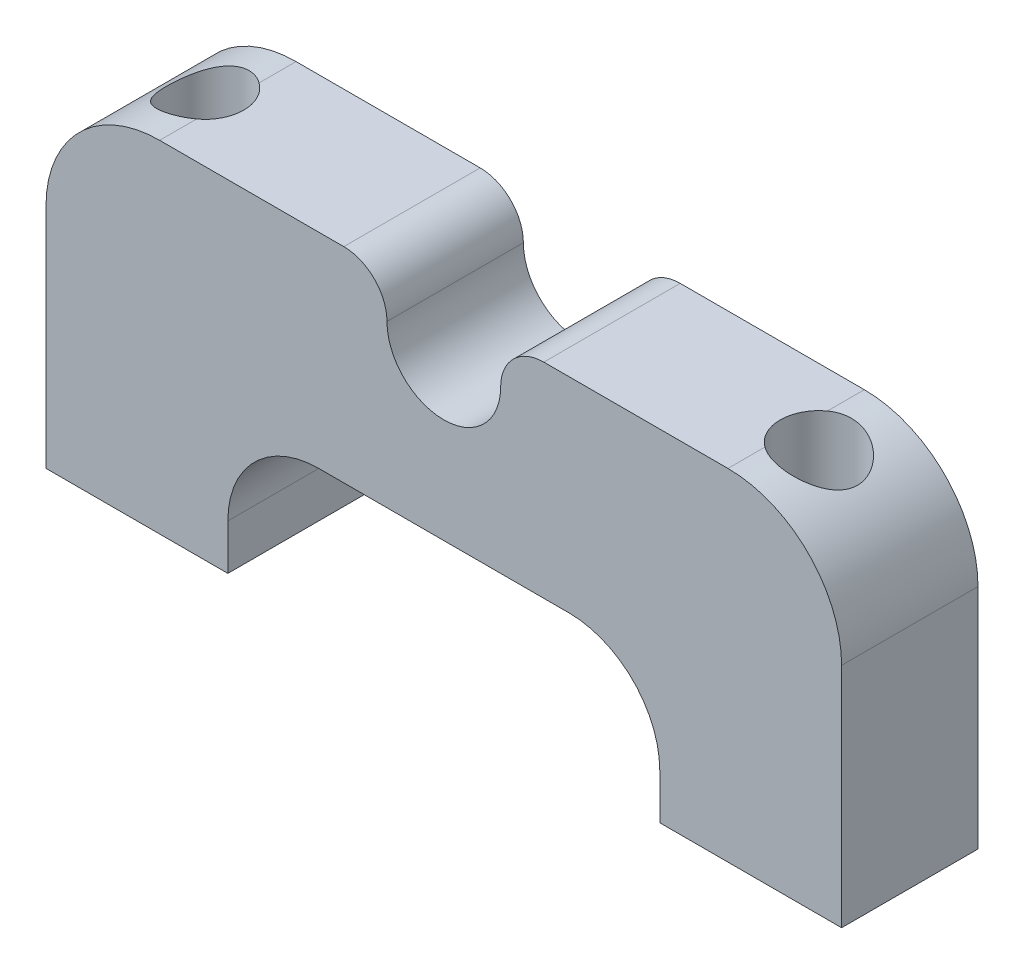
SolidWorks part; units mm, degrees
material "PEI"
ref_plane "Front Plane" through (0, 0, 0) normal (0, 0, 1) x (1, 0, 0)
ref_plane "Top Plane" through (0, 0, 0) normal (0, 1, 0) x (1, 0, 0)
ref_plane "Right Plane" through (0, 0, 0) normal (1, 0, 0) x (0, 0, -1)
sketch "Sketch1" plane through (0, 0, 0) normal (0, 0, 1) x (1, 0, 0)
  line L0 (0, 0) -> (0, 10.2981) construction
  line L1 (8.75, -3.75) -> (4.75, -3.75)
  line L2 (8.75, -3.75) -> (8.75, 1.25)
  line L3 (6.25, 3.75) -> (2.2, 3.75)
  line L4 (-8.75, -3.75) -> (-8.75, 1.25)
  line L5 (8.75, -3.75) -> (-8.75, 3.75) construction
  line L6 (8.75, 3.75) -> (-8.75, -3.75) construction
  line L7 (0, 0) -> (14.5385, 0) construction
  line L8 (-4.75, -3.75) -> (-4.75, 3.75) construction
  line L9 (-2.2, 3.75) -> (-6.25, 3.75)
  line L11 (-2.75, -0.75) -> (2.75, -0.75)
  line L13 (4.75, -3.75) -> (4.75, 3.75) construction
  line L14 (-4.75, -3.75) -> (-4.75, -2.75)
  line L15 (4.75, -3.75) -> (4.75, -2.75)
  line L16 (-4.75, -3.75) -> (-8.75, -3.75)
  arc A0 (-2.75, -0.75) -> (-4.75, -2.75) centre (-2.75, -2.75) ccw
  arc A1 (2.75, -0.75) -> (4.75, -2.75) centre (2.75, -2.75) cw
  arc A2 (8.75, 1.25) -> (6.25, 3.75) centre (6.25, 1.25) ccw
  arc A3 (-6.25, 3.75) -> (-8.75, 1.25) centre (-6.25, 1.25) ccw
  arc A4 (-1.25, 2.8) -> (1.25, 2.8) centre (0, 2.8) ccw
  arc A5 (1.25, 2.8) -> (2.2, 3.75) centre (2.2, 2.8) cw
  arc A6 (-1.25, 2.8) -> (-2.2, 3.75) centre (-2.2, 2.8) ccw
  point P0 (0, 0)
  point P32 (-0.8124, 3.75)
  dimension "D9" = 2
  dimension "D8" = 2.5
  dimension "D5" = 3
  dimension "D11" = 2.5
  dimension "D12" = 0.95
  dimension "D1" = 7.5
  dimension "D2" = 17.5
  dimension "D3" = 5.5
  dimension "D4" = 2.75
  dimension "D6" = 4
  dimension "D7" = 4
  dimension "D10" = 6.55
extrude "Boss-Extrude1" add sketch "Sketch1" along normal blind 3
hole_wizard "CSK for M1.6 Countersunk Flat Head Screw1" positions "Sketch3" profile "Sketch2" countersink size "M1.6" standard "ISO" end condition through all
sketch "Sketch3" plane through (0, -3.75, 0) normal (0, -1, 0) x (-1, 0, 0)
  line L0 (8.75, -3) -> (8.75, 0) construction
  line L1 (-8.75, -3) -> (-8.75, 0) construction
  point P0 (6.75, -1.5)
  point P2 (-6.75, -1.5)
  dimension "D1" = 2
  dimension "D2" = 2
sketch "Sketch2" plane through (-6.75, -3.75, 1.5) normal (1, 0, 0) x (0, 0, -1)
  line L0 (0, 0) -> (0, 7.5)
  line L1 (0, 7.5) -> (0.85, 7.5)
  line L2 (0.85, 7.5) -> (0.85, 0.15)
  line L3 (0.85, 0.15) -> (1, 0)
  line L5 (1, 0) -> (0, 0)
  line L6 (-0.85, 0.15) -> (-1, 0) construction
  line L11 (0, -6.35) -> (0, 107.95) construction
  dimension "Thru Hole Dia." = 1.7
  dimension "Thru Hole Depth" = 7.5
  dimension "Near C'Sink Dia." = 2
  dimension "Near C'Sink Angle" = 90
